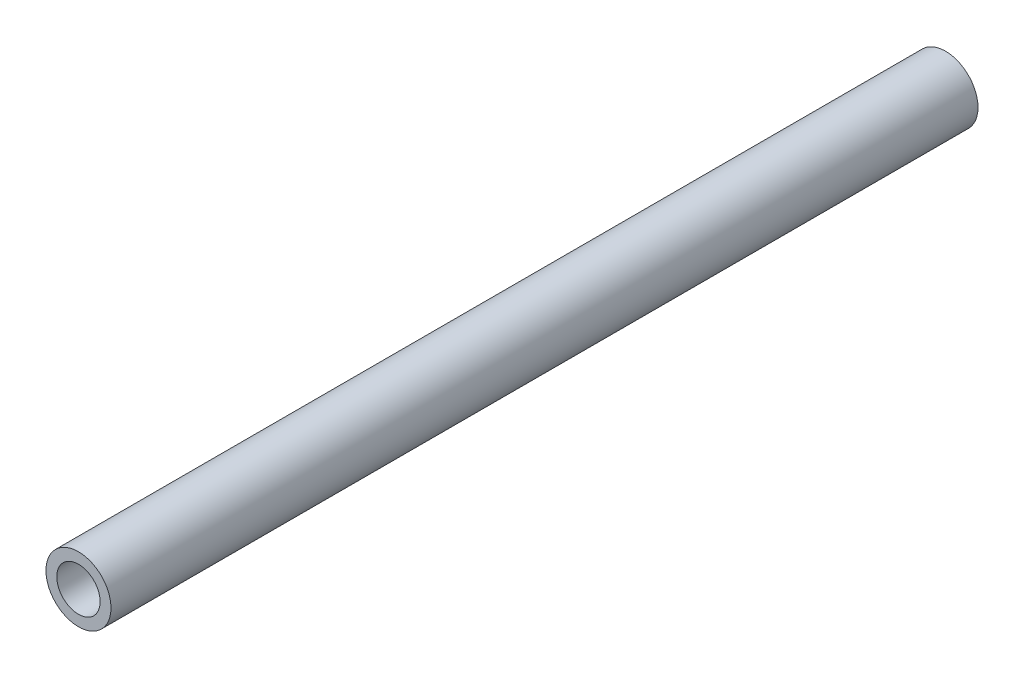
SolidWorks part; units mm, degrees
ref_plane "前视基准面" through (0, 0, 0) normal (0, 0, 1) x (1, 0, 0)
ref_plane "上视基准面" through (0, 0, 0) normal (0, 1, 0) x (1, 0, 0)
ref_plane "右视基准面" through (0, 0, 0) normal (1, 0, 0) x (0, 0, -1)
sketch "草图1" plane through (0, 0, 0) normal (0, 0, 1) x (1, 0, 0)
  circle A0 centre (0, 0) radius 5
  circle A1 centre (0, 0) radius 7.5
  dimension "D1" = 10
  dimension "D2" = 15
extrude "凸台-拉伸1" add sketch "草图1" along normal blind 200
